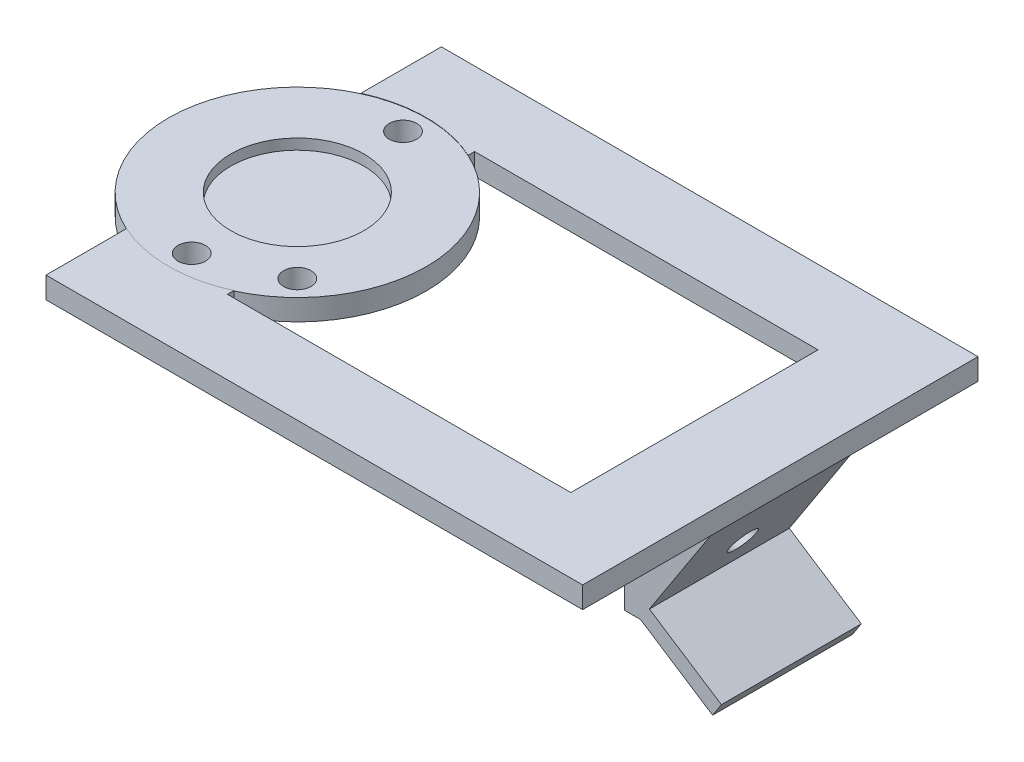
SolidWorks part; units mm, degrees
ref_plane "Front Plane" through (0, 0, 0) normal (0, 0, 1) x (1, 0, 0)
ref_plane "Top Plane" through (0, 0, 0) normal (0, 1, 0) x (1, 0, 0)
ref_plane "Right Plane" through (0, 0, 0) normal (1, 0, 0) x (0, 0, -1)
sketch "Sketch1" plane through (0, 0, 0) normal (0, 1, 0) x (1, 0, 0)
  circle A0 centre (0, 0) radius 30.5
extrude "Boss-Extrude1" add sketch "Sketch1" along normal blind 5
sketch "Sketch2" plane through (0, 5, 0) normal (0, 1, 0) x (1, 0, 0)
  circle A0 centre (0, 0) radius 15.75
extrude "Cut-Extrude1" cut sketch "Sketch2" against normal blind 2.5
sketch "Sketch3" plane through (0, 0, 0) normal (0, -1, 0) x (1, 0, 0)
  circle A0 centre (0, 0) radius 15.75
extrude "Boss-Extrude2" add sketch "Sketch3" along normal blind 2.5
sketch "Sketch4" plane through (0, 0, 0) normal (0, -1, 0) x (-1, 0, 0)
  circle A0 centre (0, 25) radius 3.25
  point P0 (0, 25)
  dimension "D1" = 25
extrude "Cut-Extrude2" cut sketch "Sketch4" against normal blind 5.08
sketch "Sketch5" plane through (0, 0, 0) normal (0, -1, 0) x (1, 0, 0)
  circle A0 centre (0, 25) radius 3.25
  point P0 (0, 25)
  dimension "D1" = 25
extrude "Cut-Extrude3" cut sketch "Sketch5" against normal blind 5.08
sketch "Sketch6" plane through (0, 0, 0) normal (0, -1, 0) x (1, 0, 0)
  circle A0 centre (0, 25) radius 3.25 construction
  circle A1 centre (17.6745, 17.6809) radius 3.25
  point P0 (17.6745, 17.6809)
  dimension "D1" = 25
  dimension "D2" = 19.13
extrude "Cut-Extrude4" cut sketch "Sketch6" against normal blind 5.08
sketch "Sketch7" plane through (0, 0, 0) normal (0, -1, 0) x (-1, 0, 0)
  line L0 (0, 0) -> (0, -30.5)
  line L1 (-12.7, -27.7301) -> (12.7, -27.7301)
  line L2 (-12.7, -27.7301) -> (-12.7, -46.7801)
  line L3 (-12.7, -46.7801) -> (12.7, -46.7801)
  line L4 (12.7, -27.7301) -> (12.7, -46.7801)
  circle A0 centre (0, 0) radius 30.5 construction
  circle M10 centre (0, 0) radius 30.5
  dimension "D1" = 25.4
  dimension "D2" = 12.7
  dimension "D3" = 19.05
extrude "Boss-Extrude3" add sketch "Sketch7" against normal blind 5.08 contours L4 L2 L3 M10
sketch "Sketch8" plane through (0, 0, 0) normal (0, -1, 0) x (1, 0, 0)
  line L0 (0, 0) -> (0, -30.5)
  line L1 (-12.7, -27.7301) -> (12.7, -27.7301)
  line L2 (-12.7, -27.7301) -> (-12.7, -46.7801)
  line L3 (-12.7, -46.7801) -> (12.7, -46.7801)
  line L4 (12.7, -27.7301) -> (12.7, -46.7801)
  arc A0 (-12.7, 27.7301) -> (12.7, 27.7301) centre (0, 0) ccw construction
  dimension "D1" = 25.4
  dimension "D2" = 12.7
  dimension "D3" = 19.05
extrude "Boss-Extrude4" add sketch "Sketch8" against normal blind 5.08
sketch "Sketch9" plane through (12.7, 0, 0) normal (1, 0, 0) x (0, 0, -1)
  line L0 (27.7301, 5.08) -> (46.7801, 5.08) construction
  line L1 (46.7801, 0) -> (29.2541, 0)
  line L2 (46.7801, 0) -> (46.7801, 5.08)
  line L3 (46.7801, 5.08) -> (29.2541, 5.08)
  line L4 (29.2541, 0) -> (29.2541, 5.08)
  dimension "D1" = 17.526
extrude "Boss-Extrude5" add sketch "Sketch9" along normal blind 101.6
sketch "Sketch10" plane through (12.7, 0, 0) normal (1, 0, 0) x (0, 0, -1)
  line L0 (-27.7301, 5.08) -> (-46.7801, 5.08) construction
  line L1 (-46.7801, 0) -> (-29.2541, 0)
  line L2 (-46.7801, 0) -> (-46.7801, 5.08)
  line L3 (-46.7801, 5.08) -> (-29.2541, 5.08)
  line L4 (-29.2541, 0) -> (-29.2541, 5.08)
  dimension "D1" = 17.526
extrude "Boss-Extrude6" add sketch "Sketch10" along normal blind 101.6
sketch "Sketch11" plane through (0, 0, 29.2541) normal (0, 0, -1) x (-1, 0, 0)
  line L0 (-114.3, 5.08) -> (-12.7, 5.08) construction
  line L1 (-114.3, 0) -> (-93.98, 0)
  line L2 (-114.3, 0) -> (-114.3, 5.08)
  line L3 (-114.3, 5.08) -> (-93.98, 5.08)
  line L4 (-93.98, 0) -> (-93.98, 5.08)
  dimension "D1" = 20.32
extrude "Boss-Extrude7" add sketch "Sketch11" along normal blind 63.5
sketch "Sketch12" plane through (0, 0, 0) normal (0, -1, 0) x (1, 0, 0)
  line L0 (93.98, -29.2541) -> (93.98, 29.2541) construction
  line L1 (93.98, -16.5541) -> (114.3, -16.5541)
  line L2 (93.98, -16.5541) -> (93.98, 16.5541)
  line L3 (93.98, 16.5541) -> (114.3, 16.5541)
  line L4 (114.3, -16.5541) -> (114.3, 16.5541)
  line L5 (114.3, 46.7801) -> (114.3, -46.7801) construction
  line L6 (93.98, -29.2541) -> (12.7, -29.2541) construction
  line L7 (93.98, 29.2541) -> (12.7, 29.2541) construction
  dimension "D1" = 12.7
  dimension "D2" = 12.7
extrude "Boss-Extrude8" add sketch "Sketch12" along normal blind 25.4
sketch "Sketch13" plane through (0, 0, 16.5541) normal (0, 0, 1) x (1, 0, 0)
  line L0 (114.3, -25.4) -> (97.79, -25.4)
  line L1 (114.3, -25.4) -> (93.98, -25.4) construction
  line L2 (97.79, -25.4) -> (114.3, 0)
  line L3 (114.3, 0) -> (114.3, -25.4)
  dimension "D1" = 3.81
extrude "Cut-Extrude5" cut sketch "Sketch13" against normal blind 33.274
sketch "Sketch14" plane through (0, 0, 16.5541) normal (0, 0, 1) x (1, 0, 0)
  line L0 (93.98, 0) -> (93.98, -17.78)
  line L1 (93.98, -25.4) -> (93.98, 0) construction
  line L2 (93.98, -17.78) -> (106.68, 0)
  line L3 (114.3, 0) -> (93.98, 0) construction
  line L4 (106.68, 0) -> (93.98, 0)
  dimension "D1" = 7.62
  dimension "D2" = 7.62
extrude "Cut-Extrude6" cut sketch "Sketch14" against normal blind 33.274
sketch "Sketch16" plane through (80.3515, -52.2285, 0) normal (0.8384, -0.545, 0) x (0, 0, -1)
  line L0 (-16.5541, 62.2922) -> (-16.5541, 31.9979) construction
  line L1 (16.5541, 31.9979) -> (-16.5541, 31.9979)
  line L2 (16.5541, 31.9979) -> (16.5541, 35.8079)
  line L3 (16.5541, 35.8079) -> (-16.5541, 35.8079)
  line L4 (-16.5541, 31.9979) -> (-16.5541, 35.8079)
  dimension "D1" = 3.81
extrude "Boss-Extrude9" add sketch "Sketch16" along normal blind 20.32
sketch "Sketch18" plane through (80.3515, -52.2285, 0) normal (0.8384, -0.545, 0) x (0, 0, -1)
  line L0 (0, 35.8079) -> (0, 62.2922)
  line L1 (16.5541, 35.8079) -> (-16.5541, 35.8079) construction
  line L2 (16.5541, 62.2922) -> (-16.5541, 62.2922) construction
  circle A0 centre (0, 45.9679) radius 3.302
  dimension "D1" = 10.16
extrude "Cut-Extrude7" cut sketch "Sketch18" against normal blind 7.62 contours L0 A0 | L0 A0
sketch "Sketch20" plane through (70.6395, -50.4568, 0) normal (-0.8137, 0.5812, 0) x (0, 0, 1)
  circle A0 centre (0, 49.8234) radius 4.826
extrude "Cut-Extrude9" cut sketch "Sketch20" against normal blind 2.54
